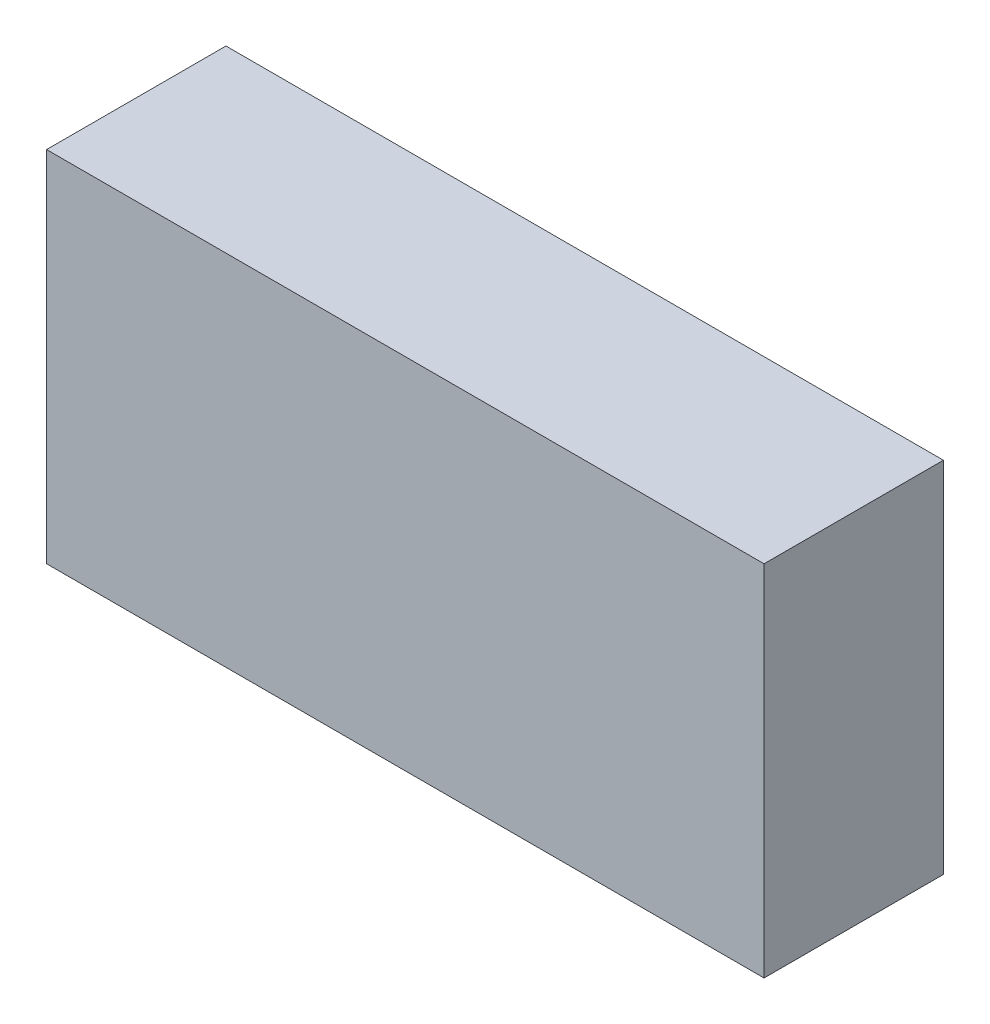
SolidWorks part; units mm, degrees
ref_plane "Front Plane" through (0, 0, 0) normal (0, 0, 1) x (1, 0, 0)
ref_plane "Top Plane" through (0, 0, 0) normal (0, 1, 0) x (1, 0, 0)
ref_plane "Right Plane" through (0, 0, 0) normal (1, 0, 0) x (0, 0, -1)
sketch "Sketch1" plane through (0, 0, 0) normal (0, 0, 1) x (1, 0, 0)
  line L1 (-20, -10) -> (20, -10)
  line L2 (-20, -10) -> (-20, 10)
  line L3 (-20, 10) -> (20, 10)
  line L4 (20, -10) -> (20, 10)
  line L5 (-20, -10) -> (20, 10) construction
  line L6 (-20, 10) -> (20, -10) construction
  point P0 (0, 0)
extrude "Boss-Extrude1" add sketch "Sketch1" along normal blind 10
